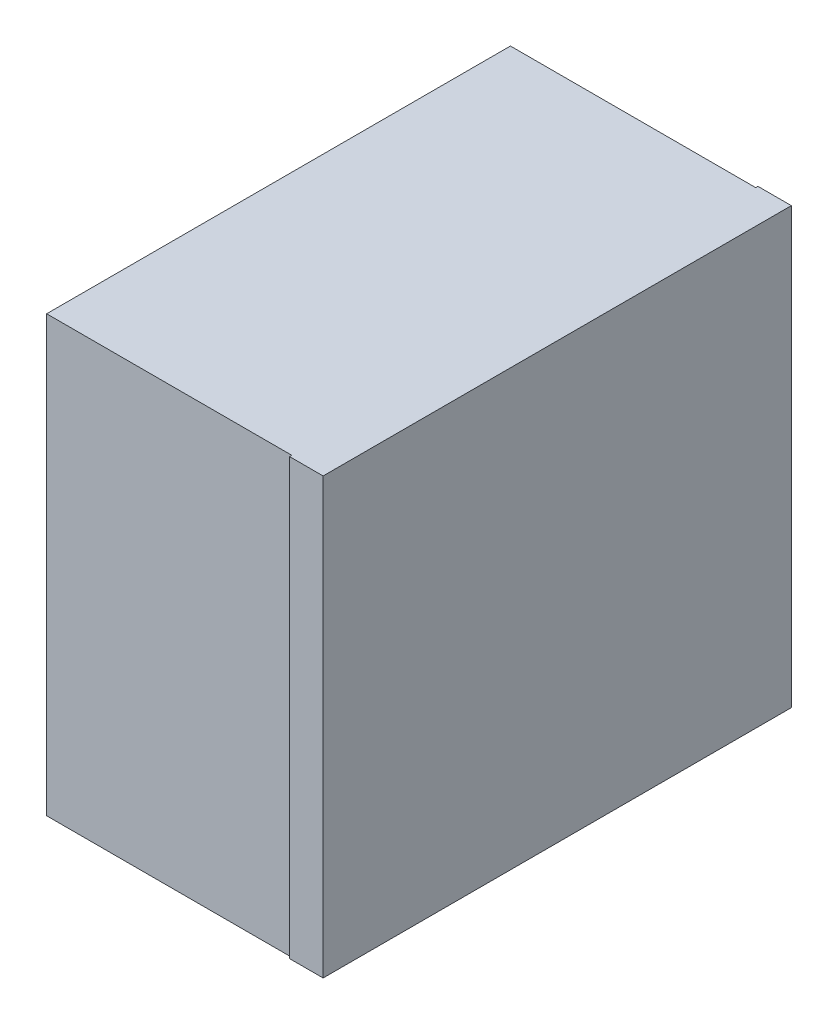
SolidWorks part; units mm, degrees
ref_plane "Alzado" through (0, 0, 0) normal (0, 0, 1) x (1, 0, 0)
ref_plane "Planta" through (0, 0, 0) normal (0, 1, 0) x (1, 0, 0)
ref_plane "Vista lateral" through (0, 0, 0) normal (1, 0, 0) x (0, 0, -1)
sketch "Croquis2" plane through (0, 0, 0) normal (0, 0, 1) x (1, 0, 0)
  line L1 (-42.5, -42.5) -> (42.5, -42.5)
  line L2 (-42.5, -42.5) -> (-42.5, 42.5)
  line L3 (-42.5, 42.5) -> (42.5, 42.5)
  line L4 (42.5, -42.5) -> (42.5, 42.5)
  line L5 (-42.5, -42.5) -> (42.5, 42.5) construction
  line L6 (-42.5, 42.5) -> (42.5, -42.5) construction
  point P0 (0, 0)
  dimension "D1" = 85
  dimension "D2" = 85
extrude "Saliente-Extruir1" add sketch "Croquis2" along normal blind 110 contours L3 L4 L1 L2
ref_plane "Plano1" through (-42.5, 0, 0) normal (-1, 0, 0) x (0, 0, 1)
sketch "Croquis3" plane through (-42.5, 0, 0) normal (-1, 0, 0) x (0, 0, 1)
  line L0 (110, -42.5) -> (90, -42.5)
  line L1 (110, -42.5) -> (0, -42.5) construction
  line L2 (90, -42.5) -> (90, 42.5)
  line L3 (110, 42.5) -> (0, 42.5) construction
  line L4 (90, 42.5) -> (110, 42.5)
  line L5 (110, 42.5) -> (110, -42.5)
  line L6 (85, -42.5) -> (85, 42.5)
  line L7 (85, 42.5) -> (78, 42.5)
  line L8 (78, 42.5) -> (78, -42.5)
  line L9 (78, -42.5) -> (85, -42.5)
  line L10 (73, 42.5) -> (73, -42.5)
  line L11 (73, -42.5) -> (66, -42.5)
  line L12 (66, -42.5) -> (66, 42.5)
  line L13 (66, 42.5) -> (73, 42.5)
  dimension "D1" = 20
  dimension "D2" = 7
  dimension "D3" = 5
  dimension "D4" = 5
  dimension "D5" = 7
extrude "Cortar-Extruir1" cut sketch "Croquis3" against normal blind 2
ref_plane "Plano2" through (0, 42.5, 0) normal (0, 1, 0) x (1, 0, 0)
sketch "Croquis5" plane through (0, 42.5, 0) normal (0, 1, 0) x (1, 0, 0)
  line L0 (-40.5, -90) -> (42.5, -90)
  line L1 (42.5, -110) -> (42.5, 0) construction
  line L2 (42.5, -90) -> (42.5, -110)
  line L3 (42.5, -110) -> (-40.5, -110)
  line L4 (-40.5, -110) -> (-40.5, -90)
  line L5 (-40.5, -85) -> (42.5, -85)
  line L6 (42.5, -85) -> (42.5, -78)
  line L7 (42.5, -78) -> (-40.5, -78)
  line L8 (-40.5, -78) -> (-40.5, -85)
  line L9 (-40.5, -73) -> (42.5, -73)
  line L10 (-40.5, -73) -> (-40.5, -66)
  line L11 (-40.5, -66) -> (42.5, -66)
  line L12 (42.5, -66) -> (42.5, -73)
extrude "Cortar-Extruir2" cut sketch "Croquis5" against normal blind 2
ref_plane "Plano3" through (42.5, 0, 0) normal (1, 0, 0) x (0, 0, -1)
sketch "Croquis6" plane through (42.5, 0, 0) normal (1, 0, 0) x (0, 0, -1)
  line L0 (-110, 40.5) -> (-110, -42.5)
  line L1 (-110, -42.5) -> (-90, -42.5)
  line L2 (-90, -42.5) -> (-90, 40.5)
  line L3 (-90, 40.5) -> (-110, 40.5)
  line L4 (-85, 40.5) -> (-85, -42.5)
  line L5 (-85, 40.5) -> (-78, 40.5)
  line L6 (-78, 40.5) -> (-78, -42.5)
  line L7 (-110, -42.5) -> (0, -42.5) construction
  line L8 (-78, -42.5) -> (-85, -42.5)
  line L9 (-73, 40.5) -> (-66, 40.5)
  line L10 (-66, 40.5) -> (-66, -42.5)
  line L11 (-66, -42.5) -> (-73, -42.5)
  line L12 (-73, -42.5) -> (-73, 40.5)
extrude "Cortar-Extruir3" cut sketch "Croquis6" against normal blind 2
ref_plane "Plano4" through (0, -42.5, 0) normal (0, -1, 0) x (-1, 0, 0)
sketch "Croquis7" plane through (0, -42.5, 0) normal (0, -1, 0) x (-1, 0, 0)
  line L0 (-40.5, -90) -> (-40.5, -110)
  line L1 (-40.5, -110) -> (40.5, -110)
  line L2 (40.5, -110) -> (40.5, -90)
  line L3 (40.5, -90) -> (-40.5, -90)
  line L4 (-40.5, -85) -> (-40.5, -78)
  line L5 (-40.5, -78) -> (40.5, -78)
  line L6 (40.5, -78) -> (40.5, -85)
  line L7 (40.5, -85) -> (-40.5, -85)
  line L8 (-40.5, -73) -> (-40.5, -66)
  line L9 (-40.5, -66) -> (40.5, -66)
  line L10 (40.5, -66) -> (40.5, -73)
  line L11 (40.5, -73) -> (-40.5, -73)
extrude "Cortar-Extruir4" cut sketch "Croquis7" against normal blind 2
ref_plane "Plano5" through (0, 0, 0) normal (0, 0, -1) x (-1, 0, 0)
sketch "Croquis8" plane through (0, 0, 0) normal (0, 0, -1) x (-1, 0, 0)
  line L0 (42.5, -2.75) -> (42.5, 2.75) construction
  line L1 (42.5, 7.5) -> (19.5, 7.5)
  line L2 (42.5, 7.5) -> (42.5, -22.5)
  line L3 (42.5, -22.5) -> (19.5, -22.5)
  line L4 (19.5, 7.5) -> (19.5, -22.5)
  line L5 (-2.75, -42.5) -> (2.75, -42.5) construction
  line L7 (-19.5, 7.5) -> (-19.5, -22.5)
  line L8 (-42.5, -22.5) -> (-19.5, -22.5)
  line L9 (-42.5, 7.5) -> (-42.5, -22.5)
  line L10 (-42.5, 7.5) -> (-19.5, 7.5)
  line L11 (-28.5, 7.5) -> (-28.5, -1.5)
  line L14 (19.5, -1.5) -> (28.5, -1.5)
  line L15 (28.5, 7.5) -> (28.5, -1.5)
  line L16 (-19.5, -1.5) -> (-28.5, -1.5)
  dimension "D1" = 23
  dimension "D2" = 30
  dimension "D3" = 20
  dimension "D4" = 9
  dimension "D5" = 9
extrude "Cortar-Extruir6" cut sketch "Croquis8" against normal blind 2 contours L7 L16 L11 L10 L9 L8 | L1 L15 L14 L4 L3 L2
ref_plane "Plano6" through (0, 0, 0) normal (0, 0, -1) x (-1, 0, 0)
sketch "Croquis12" plane through (0, 0, 0) normal (0, 0, -1) x (-1, 0, 0)
  line L1 (-28.5, 7.5) -> (-19.5, 7.5)
  line L2 (-28.5, 7.5) -> (-28.5, -1.5)
  line L3 (-28.5, -1.5) -> (-19.5, -1.5)
  line L4 (-19.5, 7.5) -> (-19.5, -1.5)
  line L5 (28.5, 7.5) -> (19.5, 7.5)
  line L6 (28.5, 7.5) -> (28.5, -1.5)
  line L7 (28.5, -1.5) -> (19.5, -1.5)
  line L8 (19.5, 7.5) -> (19.5, -1.5)
extrude "Cortar-Extruir7" cut sketch "Croquis12" against normal blind 2.5
ref_plane "Plano7" through (-11, 0, 0) normal (1, 0, 0) x (0, 0, -1)
sketch "Croquis15" plane through (-11, 0, 0) normal (1, 0, 0) x (0, 0, -1)
  line L0 (0, 17) -> (18.5, 17)
  line L1 (0, -46.75) -> (0, 46.75) construction
  line L2 (18.5, 17) -> (18.5, 25.5)
  line L3 (18.5, 25.5) -> (28.5, 25.5)
  line L4 (28.5, 25.5) -> (28.5, 34)
  line L5 (28.5, 34) -> (10, 34)
  line L6 (10, 34) -> (10, 25.5)
  line L7 (10, 25.5) -> (0, 25.5)
  line L8 (36.3, 42.5) -> (-36.3, 42.5) construction
  line L9 (0, 25.5) -> (0, 17)
  point P4 (10, 29.75)
  dimension "D1" = 18.5
  dimension "D2" = 8.5
  dimension "D3" = 8.5
  dimension "D4" = 8.5
  dimension "D5" = 17
  dimension "D6" = 8.5
  dimension "19" = 18.5
extrude "Saliente-Extruir3" add sketch "Croquis15" against normal blind 10 contours L5 L6 L7 L9 L0 L2 L3 L4
ref_plane "Plano8" through (11, 0, 0) normal (1, 0, 0) x (0, 0, -1)
sketch "Croquis18" plane through (11, 0, 0) normal (1, 0, 0) x (0, 0, -1)
  line L0 (18.5, 17) -> (18.5, 25.5)
  line L1 (18.5, 25.5) -> (28.5, 25.5)
  line L2 (28.5, 25.5) -> (28.5, 34)
  line L3 (28.5, 34) -> (10, 34)
  line L4 (10, 34) -> (10, 25.5)
  line L5 (10, 25.5) -> (0, 25.5)
  line L6 (0, -46.75) -> (0, 46.75) construction
  line L7 (10, 25.5) -> (0, 25.5) construction
  line L8 (0, 25.5) -> (0, 17)
  line L9 (0, 17) -> (18.5, 17) construction
  line L10 (0, 17) -> (18.5, 17)
extrude "Saliente-Extruir4" add sketch "Croquis18" along normal blind 10
ref_plane "Plano9" through (0, 42.5, 0) normal (0, 1, 0) x (1, 0, 0)
sketch "Croquis19" plane through (0, 42.5, 0) normal (0, 1, 0) x (1, 0, 0)
  line L0 (60.5, -59.3707) -> (49.5, -59.3707)
  line L2 (42.5, -36.3) -> (42.5, 36.3) construction
  line L4 (60.5, -17.0524) -> (60.5, -24.0524)
  line L5 (60.5, -24.0524) -> (71.5, -24.0524)
  line L6 (49.5, -59.3707) -> (49.5, -52.3707)
  line L7 (71.5, -31.0524) -> (82.5, -31.0524)
  line L8 (82.5, -31.0524) -> (82.5, -38.0524)
  line L9 (82.5, -38.0524) -> (89.5, -38.0524)
  line L10 (89.5, -38.0524) -> (89.5, -58.0524)
  line L11 (89.5, -58.0524) -> (82.5, -58.0524)
  line L12 (82.5, -58.0524) -> (82.5, -73.3707)
  line L13 (82.5, -73.3707) -> (71.5, -73.3707)
  line L14 (71.5, -73.3707) -> (71.5, -66.3707)
  line L15 (71.5, -66.3707) -> (60.5, -66.3707)
  line L16 (60.5, -66.3707) -> (60.5, -59.3707)
  line L17 (49.5, -52.3707) -> (42.5, -52.3707)
  line L18 (42.5, -52.3707) -> (42.5, -24.0524)
  line L19 (71.5, -24.0524) -> (71.5, -31.0524)
  line L20 (42.5, -24.0524) -> (49.5, -24.0524)
  line L21 (49.5, -24.0524) -> (49.5, -17.0524)
  line L22 (49.5, -17.0524) -> (60.5, -17.0524)
  line L23 (0, 0) -> (0, -28.8645) construction
  line L24 (-49.5, -17.0524) -> (-60.5, -17.0524)
  line L25 (-49.5, -24.0524) -> (-49.5, -17.0524)
  line L26 (-42.5, -24.0524) -> (-49.5, -24.0524)
  line L27 (-71.5, -24.0524) -> (-71.5, -31.0524)
  line L28 (-42.5, -52.3707) -> (-42.5, -24.0524)
  line L29 (-49.5, -52.3707) -> (-42.5, -52.3707)
  line L30 (-60.5, -66.3707) -> (-60.5, -59.3707)
  line L31 (-71.5, -66.3707) -> (-60.5, -66.3707)
  line L32 (-71.5, -73.3707) -> (-71.5, -66.3707)
  line L33 (-82.5, -73.3707) -> (-71.5, -73.3707)
  line L34 (-82.5, -58.0524) -> (-82.5, -73.3707)
  line L35 (-89.5, -58.0524) -> (-82.5, -58.0524)
  line L36 (-89.5, -38.0524) -> (-89.5, -58.0524)
  line L37 (-82.5, -38.0524) -> (-89.5, -38.0524)
  line L38 (-82.5, -31.0524) -> (-82.5, -38.0524)
  line L39 (-71.5, -31.0524) -> (-82.5, -31.0524)
  line L40 (-49.5, -59.3707) -> (-49.5, -52.3707)
  line L41 (-60.5, -24.0524) -> (-71.5, -24.0524)
  line L42 (-60.5, -17.0524) -> (-60.5, -24.0524)
  line L43 (-60.5, -59.3707) -> (-49.5, -59.3707)
  dimension "D1" = 7
  dimension "D2" = 7
  dimension "D3" = 11
  dimension "D4" = 11
  dimension "D5" = 11
  dimension "D6" = 7
  dimension "D7" = 7
  dimension "D8" = 7
  dimension "D9" = 7
  dimension "D10" = 20
  dimension "D11" = 7
  dimension "D12" = 11
  dimension "D13" = 11
  dimension "D14" = 11
  dimension "D15" = 7
  dimension "D16" = 7
  dimension "D17" = 7
extrude "Saliente-Extruir5" add sketch "Croquis19" against normal blind 10
ref_plane "Plano10" through (0, -42.5, 0) normal (0, -1, 0) x (-1, 0, 0)
sketch "Croquis20" plane through (0, -42.5, 0) normal (0, -1, 0) x (-1, 0, 0)
  line L0 (46.75, 0) -> (-46.75, 0) construction
  line L1 (-42.5, 36.3) -> (-42.5, -36.3) construction
  line L2 (-34.5, -20) -> (-24.5, -20)
  line L3 (-34.5, -20) -> (-34.5, -30)
  line L4 (-34.5, -30) -> (-24.5, -30)
  line L5 (-24.5, -20) -> (-24.5, -30)
  line L6 (24.5, -20) -> (24.5, -30)
  line L7 (24.5, -20) -> (34.5, -20)
  line L8 (34.5, -20) -> (34.5, -30)
  line L9 (24.5, -30) -> (34.5, -30)
  line L10 (-34.5, -20) -> (24.5, -20) construction
  line L12 (42.5, -52.3707) -> (42.5, -24.0524) construction
  line L13 (-34.5, -55) -> (-24.5, -55)
  line L14 (-34.5, -55) -> (-34.5, -65)
  line L15 (-34.5, -65) -> (-24.5, -65)
  line L16 (-24.5, -55) -> (-24.5, -65)
  line L17 (24.5, -55) -> (34.5, -55)
  line L18 (24.5, -55) -> (24.5, -65)
  line L19 (24.5, -65) -> (34.5, -65)
  line L20 (34.5, -55) -> (34.5, -65)
  dimension "D1" = 10
  dimension "D2" = 10
  dimension "D3" = 10
  dimension "22" = 20
  dimension "D4" = 8
  dimension "D6" = 8
  dimension "D7" = 10
  dimension "D8" = 10
  dimension "D9" = 10
  dimension "D10" = 25
  dimension "25" = 25
  dimension "D5" = 2
extrude "Saliente-Extruir6" add sketch "Croquis20" along normal blind 25
ref_plane "Plano11" through (0, 0, 0) normal (1, 0, 0) x (0, 0, -1)
sketch "Croquis21" plane through (0, 0, 0) normal (1, 0, 0) x (0, 0, -1)
  line L5 (-114.6347, 44.7705) -> (36.0653, 44.7705)
  line L6 (-114.6347, 44.7705) -> (-114.6347, -75.9767)
  line L7 (-114.6347, -75.9767) -> (36.0653, -75.9767)
  line L8 (36.0653, 44.7705) -> (36.0653, -75.9767)
extrude "Cortar-Extruir9" cut sketch "Croquis21" along normal blind 112 contours L8 L7 L6 L5
sketch "Croquis22" plane through (0, 0, 0) normal (1, 0, 0) x (0, 0, -1)
  line L1 (61, -97.5) -> (-149, -97.5)
  line L2 (61, -97.5) -> (61, 97.5)
  line L3 (61, 97.5) -> (-149, 97.5)
  line L4 (-149, -97.5) -> (-149, 97.5)
  line L5 (61, -97.5) -> (-149, 97.5) construction
  line L6 (61, 97.5) -> (-149, -97.5) construction
  point P0 (-44, 0)
  point P5 (-47.7967, 0)
  point P6 (-46.6816, 0)
  point P7 (-46.31, 0)
  dimension "D1" = 210
  dimension "D2" = 195
  dimension "D3" = 97.5
  dimension "D4" = 149
extrude "Saliente-Extruir7" add sketch "Croquis22" along normal blind 15
ref_plane "Plano12" through (0, 0, 0) normal (-1, 0, 0) x (0, 0, 1)
sketch "Croquis23" plane through (0, 0, 0) normal (-1, 0, 0) x (0, 0, 1)
  line L0 (-61, 97.5) -> (149, -97.5) construction
  line L6 (-50, -87.5) -> (138, -87.5)
  line L7 (-50, -87.5) -> (-50, 87.5)
  line L8 (-50, 87.5) -> (138, 87.5)
  line L9 (138, -87.5) -> (138, 87.5)
  line L10 (-50, -87.5) -> (138, 87.5) construction
  line L11 (-50, 87.5) -> (138, -87.5) construction
  point P4 (44, 0)
  dimension "D1" = 188
  dimension "D2" = 175
extrude "Extruir-Lámina1" add sketch "Croquis23" along normal blind 110 thin contours L8 L9 L6 L7
sketch "Croquis24" plane through (0, 42.5, 0) normal (0, 1, 0) x (1, 0, 0)
sketch "Croquis25" plane through (0, 42.5, 0) normal (0, 1, 0) x (1, 0, 0)
  line L0 (0, -80.897) -> (0, 80.897) construction
  line L1 (23.375, 0) -> (-23.375, 0) construction
  circle A0 centre (0, -37) radius 15
  dimension "D1" = 37
extrude "Saliente-Extruir8" add sketch "Croquis25" along normal up to next draft 10 draft outward yes
sketch "Croquis26" plane through (0, 42.5, 0) normal (0, 1, 0) x (1, 0, 0)
  line L0 (0, -80.897) -> (0, 80.897) construction
  line L1 (-42.5, 0) -> (0, 0) construction
  circle A0 centre (0, -6) radius 5
  point P4 (0, -6.2284)
  dimension "D1" = 6
sketch "Croquis35" plane through (0, 0, 0) normal (1, 0, 0) x (0, 0, -1)
  line L0 (-6, 42.5) -> (10, 87.5)
  line L1 (50, 87.5) -> (-14.0653, 87.5) construction
  dimension "D1" = 16
sweep "Barrer2" add profiles "Croquis26" path "Croquis35"
ref_plane "Plano13" through (0, 0, 0) normal (-1, 0, 0) x (0, 0, 1)
sketch "Croquis37" plane through (0, 0, 0) normal (-1, 0, 0) x (0, 0, 1)
  line L1 (90, 40.5) -> (110, 40.5) construction
  line L3 (105, 71.5) -> (125, 71.5)
  line L4 (105, 55.5) -> (117, 55.5)
  line L5 (117, 55.5) -> (117, -53.5)
  line L6 (133, 63.5) -> (133, -61.5)
  line L7 (105, -53.5) -> (117, -53.5)
  line L8 (105, -69.5) -> (125, -69.5)
  line L10 (-47, 63.5) -> (-47, -61.5)
  line L11 (-19, -69.5) -> (-39, -69.5)
  line L12 (-19, -53.5) -> (-31, -53.5)
  line L13 (-31, 55.5) -> (-31, -53.5)
  line L14 (-19, 55.5) -> (-31, 55.5)
  line L15 (-19, 71.5) -> (-39, 71.5)
  line L16 (138, -87.5) -> (138, 87.5) construction
  line L17 (138, -87.5) -> (138, 87.5) construction
  arc A0 (105, 71.5) -> (105, 55.5) centre (105, 63.5) ccw
  arc A1 (133, 63.5) -> (125, 71.5) centre (125, 63.5) ccw
  arc A2 (125, -69.5) -> (133, -61.5) centre (125, -61.5) ccw
  arc A3 (105, -53.5) -> (105, -69.5) centre (105, -61.5) ccw
  arc A4 (-39, -69.5) -> (-47, -61.5) centre (-39, -61.5) cw
  arc A5 (-19, -53.5) -> (-19, -69.5) centre (-19, -61.5) cw
  arc A6 (-19, 71.5) -> (-19, 55.5) centre (-19, 63.5) cw
  arc A7 (-47, 63.5) -> (-39, 71.5) centre (-39, 63.5) cw
  dimension "D1" = 5
  dimension "D2" = 15
  dimension "D3" = 33
  dimension "D4" = 13
  dimension "D5" = 33
  dimension "D6" = 13
  dimension "D7" = 125
  dimension "D8" = 148
extrude "Saliente-Extruir9" add sketch "Croquis37" along normal blind 10 contours L7 A3 L8 A2 L6 A1 L3 A0 L4 L5 | A7 L10 A4 L11 A5 L12 L13 L14 A6 L15
